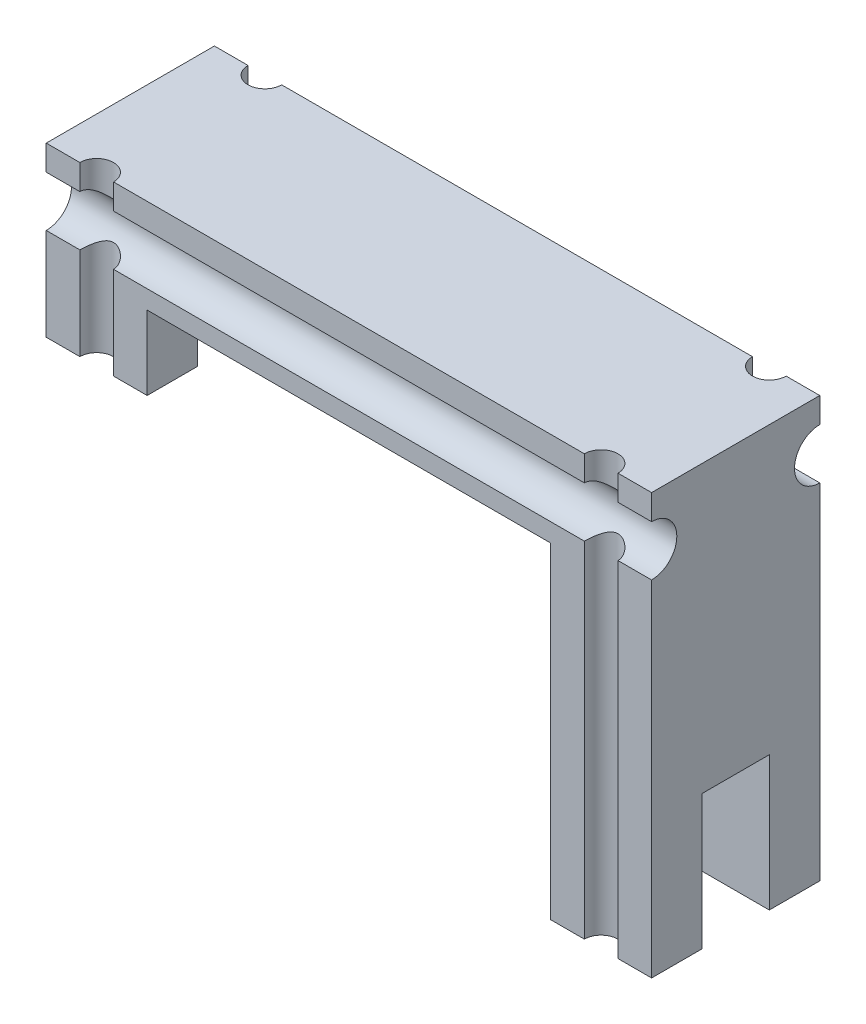
SolidWorks part; units mm, degrees
ref_plane "前视基准面" through (0, 0, 0) normal (0, 0, 1) x (1, 0, 0)
ref_plane "上视基准面" through (0, 0, 0) normal (0, 1, 0) x (1, 0, 0)
ref_plane "右视基准面" through (0, 0, 0) normal (1, 0, 0) x (0, 0, -1)
sketch "草图1" plane through (0, 0, 0) normal (0, 0, 1) x (1, 0, 0)
  line L1 (-90, 55) -> (90, 55)
  line L2 (-90, 55) -> (-90, -55)
  line L3 (-90, -55) -> (90, -55)
  line L4 (90, 55) -> (90, -55)
  line L5 (-90, 55) -> (90, -55) construction
  line L6 (-90, -55) -> (90, 55) construction
  point P0 (0, 0)
  dimension "D1" = 180
  dimension "D2" = 110
extrude "凸台-拉伸1" add sketch "草图1" along normal blind 30
sketch "草图2" plane through (0, 0, 30) normal (0, 0, 1) x (1, 0, 0)
  line L0 (90, 55) -> (-90, 55) construction
  line L1 (-90, -55) -> (60, -55)
  line L2 (-90, -55) -> (-90, 20)
  line L3 (-90, 20) -> (60, 20)
  line L4 (60, -55) -> (60, 20)
  line L5 (90, -55) -> (90, 55) construction
  dimension "D1" = 35
  dimension "D2" = 30
extrude "切除-拉伸1" cut sketch "草图2" against normal blind 30
sketch "草图3" plane through (-90, 0, 0) normal (-1, 0, 0) x (0, 0, 1)
  line L0 (0, 20) -> (30, 20) construction
  line L1 (25, 0) -> (5, 0)
  line L2 (25, 0) -> (25, 40)
  line L3 (25, 40) -> (5, 40)
  line L4 (5, 0) -> (5, 40)
  line L5 (25, 0) -> (5, 40) construction
  line L6 (25, 40) -> (5, 0) construction
  line L7 (0, 20) -> (30, 20) construction
  point P0 (15, 20)
  dimension "D1" = 20
  dimension "D2" = 20
extrude "切除-拉伸2" cut sketch "草图3" against normal up to surface (150 mm away) up to face at (60, -17.5, 15)
sketch "草图4" plane through (60, 0, 0) normal (-1, 0, 0) x (0, 0, 1)
  line L0 (0, -55) -> (30, -55) construction
  line L1 (25, -95) -> (5, -95)
  line L2 (25, -95) -> (25, -15)
  line L3 (25, -15) -> (5, -15)
  line L4 (5, -95) -> (5, -15)
  line L5 (25, -95) -> (5, -15) construction
  line L6 (25, -15) -> (5, -95) construction
  point P0 (15, -55)
  dimension "D1" = 20
  dimension "D2" = 80
extrude "切除-拉伸3" cut sketch "草图4" against normal blind 30
sketch "草图5" plane through (0, 0, 30) normal (0, 0, 1) x (1, 0, 0)
  line L0 (60, 20) -> (-90, 20) construction
  line L1 (-60, 20) -> (60, 20)
  line L2 (-60, 20) -> (-60, 42)
  line L3 (-60, 42) -> (60, 42)
  line L4 (60, 20) -> (60, 42)
  line L5 (-90, 55) -> (-90, 20) construction
  line L6 (60, -55) -> (60, 20) construction
  dimension "D1" = 22
  dimension "D2" = 30
  dimension "D3" = 0
extrude "切除-拉伸4" cut sketch "草图5" against normal blind 30
sketch "草图6" plane through (0, -15, 0) normal (0, -1, 0) x (1, 0, 0)
  line L1 (50, 20) -> (-50, 20)
  line L2 (50, 20) -> (50, 10)
  line L3 (50, 10) -> (-50, 10)
  line L4 (-50, 20) -> (-50, 10)
  line L5 (50, 20) -> (-50, 10) construction
  line L6 (50, 10) -> (-50, 20) construction
  point P0 (0, 15)
  dimension "D1" = 10
  dimension "D2" = 15
  dimension "D3" = 100
  dimension "D4" = 50
extrude "切除-拉伸5" cut sketch "草图6" against normal blind 64
sketch "草图7" plane through (0, 0, 0) normal (0, 0, -1) x (-1, 0, 0)
  line L8 (-60, 42) -> (60, 42)
  line L9 (60, 42) -> (60, 20)
  line L10 (60, 20) -> (90, 20)
  line L11 (90, 20) -> (90, 55)
  line L12 (90, 55) -> (-90, 55)
  line L13 (-90, 55) -> (-90, -55)
  line L14 (-90, -55) -> (-60, -55)
  line L15 (-60, -55) -> (-60, 42)
  line L16 (-60, 42) -> (60, 42)
  line L17 (60, 42) -> (60, 20)
  line L18 (60, 20) -> (90, 20)
  line L19 (90, 20) -> (90, 55)
  line L20 (90, 55) -> (-90, 55)
  line L21 (-90, 55) -> (-90, -55)
  line L22 (-90, -55) -> (-60, -55)
  line L23 (-60, -55) -> (-60, 42)
  dimension "D1" = 0
extrude "凸台-拉伸2" add sketch "草图7" along normal blind 10
sketch "草图8" plane through (0, 0, 30) normal (0, 0, 1) x (1, 0, 0)
  line L8 (-60, 20) -> (-60, 42)
  line L9 (-60, 42) -> (60, 42)
  line L10 (60, 42) -> (60, -55)
  line L11 (60, -55) -> (90, -55)
  line L12 (90, -55) -> (90, 55)
  line L13 (90, 55) -> (-90, 55)
  line L14 (-90, 55) -> (-90, 20)
  line L15 (-90, 20) -> (-60, 20)
  line L16 (-60, 20) -> (-60, 42)
  line L17 (-60, 42) -> (60, 42)
  line L18 (60, 42) -> (60, -55)
  line L19 (60, -55) -> (90, -55)
  line L20 (90, -55) -> (90, 55)
  line L21 (90, 55) -> (-90, 55)
  line L22 (-90, 55) -> (-90, 20)
  line L23 (-90, 20) -> (-60, 20)
  dimension "D1" = 0
extrude "凸台-拉伸3" add sketch "草图8" along normal blind 10
sketch "草图9" plane through (0, 55, 0) normal (0, 1, 0) x (1, 0, 0)
  line L4 (90, -40) -> (90, 10)
  line L5 (90, 10) -> (-90, 10)
  line L6 (-90, 10) -> (-90, -40)
  line L7 (-90, -40) -> (90, -40)
  line L8 (90, -40) -> (90, 10)
  line L9 (90, 10) -> (-90, 10)
  line L10 (-90, 10) -> (-90, -40)
  line L11 (-90, -40) -> (90, -40)
  dimension "D1" = 0
extrude "凸台-拉伸4" add sketch "草图9" along normal blind 15
sketch "草图10" plane through (0, -55, 0) normal (0, -1, 0) x (1, 0, 0)
  line L0 (60, 40) -> (90, 40) construction
  line L1 (90, -10) -> (60, -10) construction
  line L2 (-90, 40) -> (-60, 40) construction
  line L3 (-60, -10) -> (-90, -10) construction
  circle A0 centre (75, 40) radius 5
  circle A1 centre (75, -10) radius 5
  circle A2 centre (-75, 40) radius 5
  circle A3 centre (-75, -10) radius 5
  dimension "D1" = 10
  dimension "D2" = 10
  dimension "D3" = 10
  dimension "D4" = 10
extrude "切除-拉伸6" cut sketch "草图10" against normal blind 144
sketch "草图11" plane through (-90, 0, 0) normal (-1, 0, 0) x (0, 0, 1)
  line L0 (40, 70) -> (40, 20) construction
  line L1 (-10, 20) -> (-10, 70) construction
  line L2 (-10, 70) -> (40, 70) construction
  circle A0 centre (40, 55) radius 7.5
  circle A1 centre (-10, 55) radius 7.5
  dimension "D1" = 15
  dimension "D2" = 15
  dimension "D3" = 15
  dimension "D4" = 15
extrude "切除-拉伸7" cut sketch "草图11" against normal blind 191
